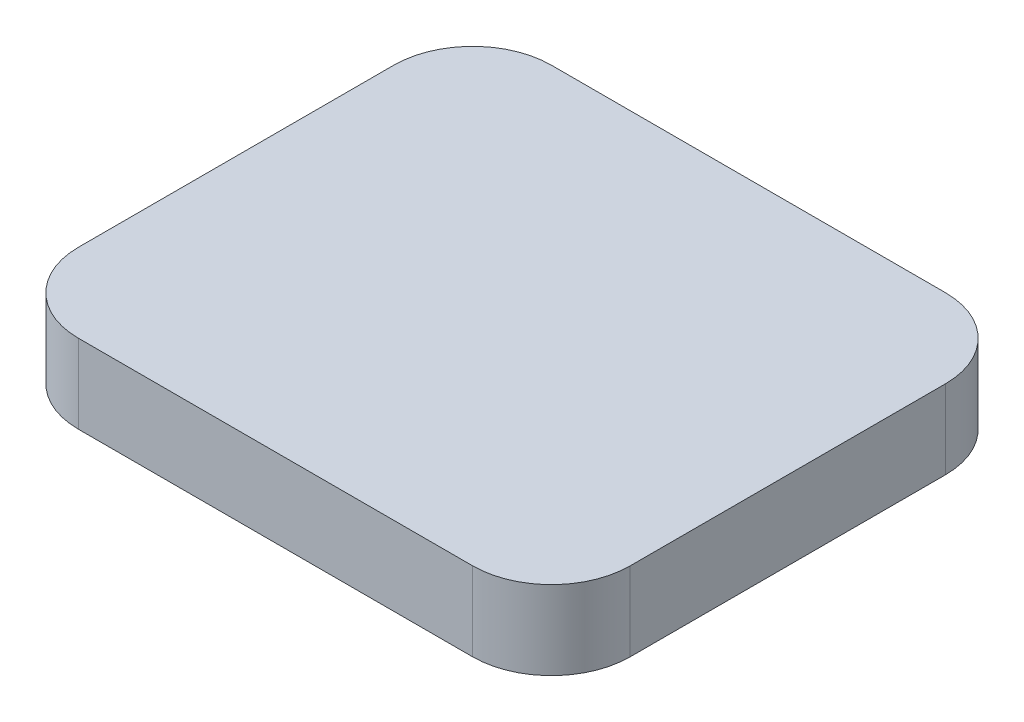
SolidWorks part; units mm, degrees
ref_plane "Plano frontal" through (0, 0, 0) normal (0, 0, 1) x (1, 0, 0)
ref_plane "Plano superior" through (0, 0, 0) normal (0, 1, 0) x (1, 0, 0)
ref_plane "Plano direito" through (0, 0, 0) normal (1, 0, 0) x (0, 0, -1)
sketch "Esboço1" plane through (0, 0, 0) normal (0, 1, 0) x (1, 0, 0)
  line L1 (-2.5, -3) -> (2.5, -3)
  line L2 (-3.5, -2) -> (-3.5, 2)
  line L3 (-2.5, 3) -> (2.5, 3)
  line L4 (3.5, -2) -> (3.5, 2)
  line L5 (-3.5, -3) -> (3.5, 3) construction
  line L6 (-3.5, 3) -> (3.5, -3) construction
  arc A0 (3.5, 2) -> (2.5, 3) centre (2.5, 2) ccw
  arc A1 (3.5, -2) -> (2.5, -3) centre (2.5, -2) cw
  arc A2 (-2.5, -3) -> (-3.5, -2) centre (-2.5, -2) cw
  arc A3 (-2.5, 3) -> (-3.5, 2) centre (-2.5, 2) ccw
  point P0 (0, 0)
  dimension "D3" = 1
  dimension "D1" = 7
  dimension "D2" = 6
extrude "Ressalto-extrusão1" add sketch "Esboço1" along normal blind 1
